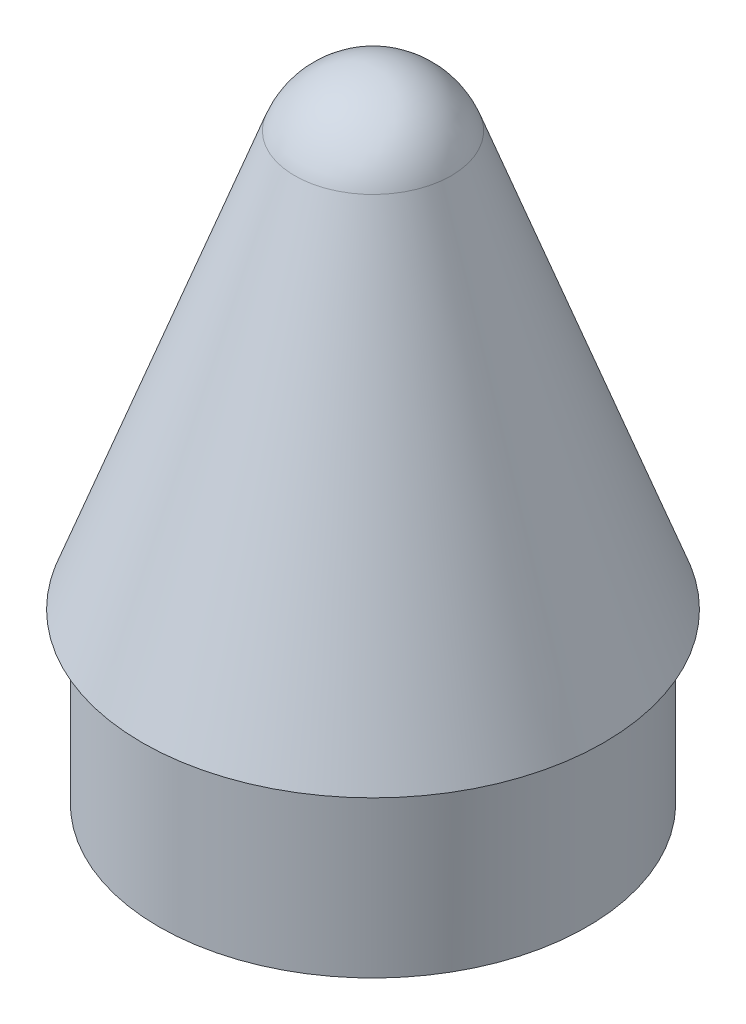
SolidWorks part; units mm, degrees
material "Polyurethane Foam Flexible"
ref_plane "Front Plane" through (0, 0, 0) normal (0, 0, 1) x (1, 0, 0)
ref_plane "Top Plane" through (0, 0, 0) normal (0, 1, 0) x (1, 0, 0)
ref_plane "Right Plane" through (0, 0, 0) normal (1, 0, 0) x (0, 0, -1)
sketch "Sketch5" plane through (0, 0, 0) normal (0, 0, 1) x (1, 0, 0)
  line L0 (0, 0) -> (-13.75, 0)
  line L1 (0, 0) -> (0, 24.7)
  line L3 (-4.6615, 24.7) -> (-13.75, 0)
  line L6 (0, 27.9518) -> (0, 24.7)
  arc A0 (-4.6615, 24.7) -> (0, 27.9518) centre (0, 22.9848) cw
revolve "Revolve2" add sketch "Sketch5" angle 360 about L1
sketch "Sketch6" plane through (0, 0, 0) normal (0, -1, 0) x (1, 0, 0)
  circle A0 centre (0, 0) radius 2.5
  circle A1 centre (0, 0) radius 12.75
extrude "Boss-Extrude2" add sketch "Sketch6" along normal blind 10
